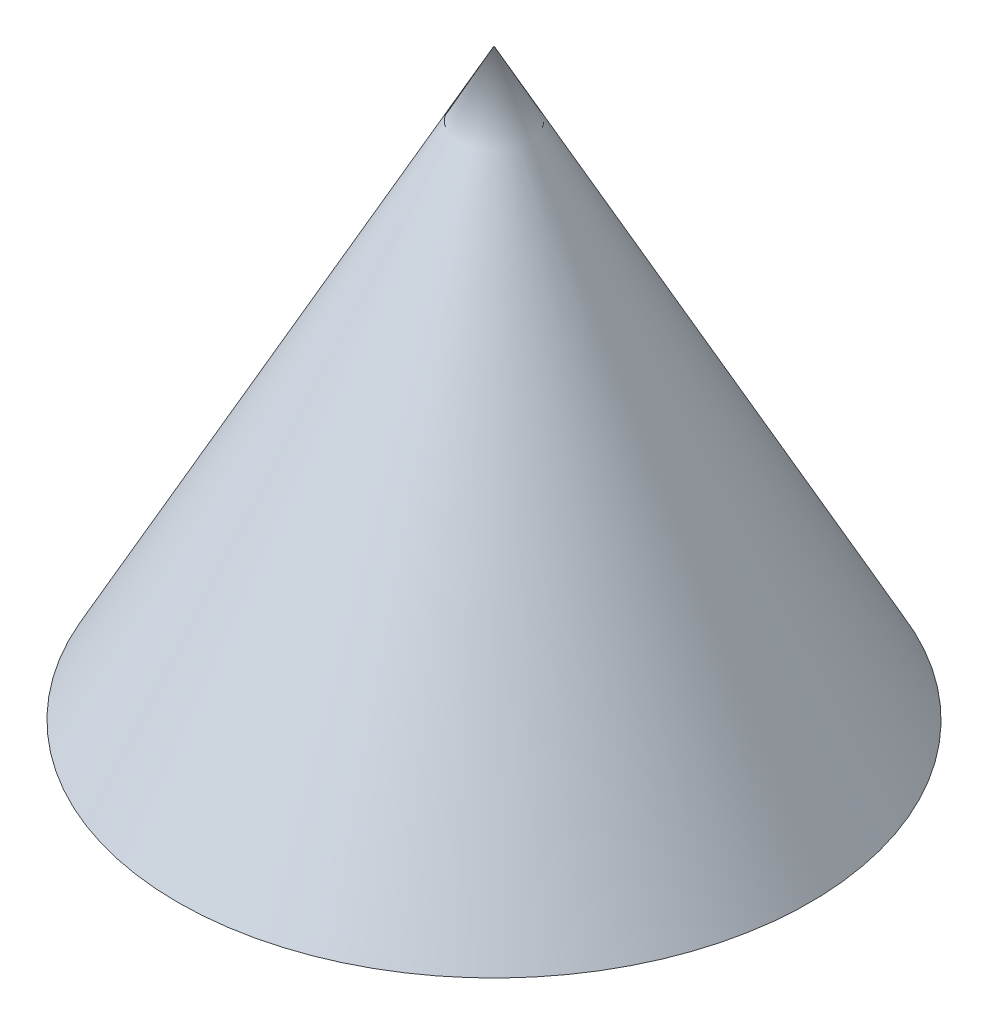
SolidWorks part; units mm, degrees
material "ABS"
ref_plane "正面" through (0, 0, 0) normal (0, 0, 1) x (1, 0, 0)
ref_plane "平面" through (0, 0, 0) normal (0, 1, 0) x (1, 0, 0)
ref_plane "右側面" through (0, 0, 0) normal (1, 0, 0) x (0, 0, -1)
sketch "ｽｹｯﾁ1" plane through (0, 0, 0) normal (0, 0, 1) x (1, 0, 0)
  line L0 (0, 0) -> (0, 6)
  line L1 (0, 6) -> (-3.25, 0)
  line L2 (-3.25, 0) -> (0, 0)
  dimension "D1" = 6
  dimension "D2" = 3.25
revolve "回転1" add sketch "ｽｹｯﾁ1" angle 360 about L0
